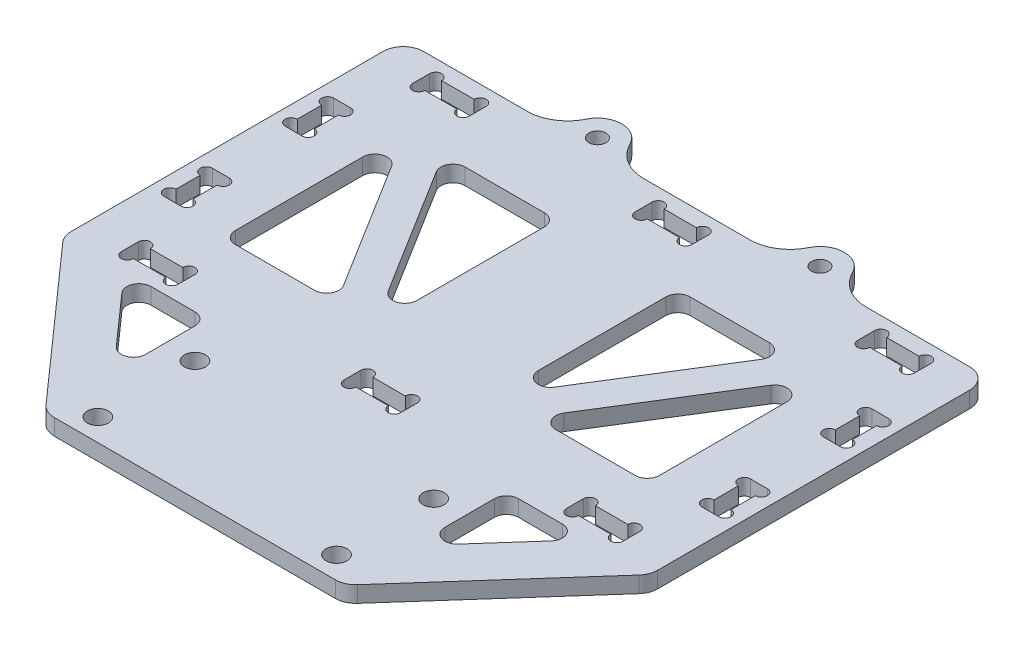
SolidWorks part; units mm, degrees
ref_plane "前视基准面" through (0, 0, 0) normal (0, 0, 1) x (1, 0, 0)
ref_plane "上视基准面" through (0, 0, 0) normal (0, 1, 0) x (1, 0, 0)
ref_plane "右视基准面" through (0, 0, 0) normal (1, 0, 0) x (0, 0, -1)
other "Configuration Table"
sketch "草图1" plane through (0, 0, 0) normal (0, 1, 0) x (1, 0, 0)
  line L0 (-37, 0) -> (37, 0)
  line L1 (37, 0) -> (37, 40)
  line L2 (37, 40) -> (72.5, 40)
  line L3 (72.5, 40) -> (72.5, 124)
  line L4 (0, 0) -> (0, 122.7817) construction
  line L5 (72.5, 124) -> (-72.5, 124)
  line L6 (-72.5, 40) -> (-72.5, 124)
  line L7 (-37, 40) -> (-72.5, 40)
  line L8 (-37, 0) -> (-37, 40)
  point P10 (0, 124)
  point P13 (0, 0)
  dimension "D1" = 74
  dimension "D2" = 40
  dimension "D3" = 84
  dimension "D4" = 145
extrude "凸台-拉伸1" add sketch "草图1" along normal blind 4
sketch "草图2" plane through (0, 4, 0) normal (0, 1, 0) x (1, 0, 0)
  line L0 (0, 0) -> (0, 124) construction
  line L1 (-37, 0) -> (37, 0) construction
  line L2 (72.5, 124) -> (-72.5, 124) construction
  line L3 (-37, 17.5) -> (37, 17.5) construction
  circle A0 centre (29.5, 5.5) radius 2.6
  circle A1 centre (-29.5, 5.5) radius 2.6
  circle A2 centre (29.5, 29.5) radius 2.6
  circle A3 centre (-29.5, 29.5) radius 2.6
  dimension "D1" = 59
  dimension "D3" = 24
  dimension "D4" = 5.2
  dimension "D2" = 17.5
extrude "切除-拉伸1" cut sketch "草图2" against normal blind 4
sketch "草图3" plane through (0, 4, 0) normal (0, 1, 0) x (1, 0, 0)
  line L19 (-72.5, 81.9) -> (72.5, 81.9) construction
  line L20 (-72.5, 124) -> (-72.5, 40) construction
  line L21 (72.5, 40) -> (72.5, 124) construction
  line L22 (-7, 43.8) -> (7, 48) construction
  line L23 (-7, 48) -> (7, 43.8) construction
  line L24 (0, 0) -> (0, 124) construction
  line L25 (-37, 0) -> (37, 0) construction
  line L26 (72.5, 124) -> (-72.5, 124) construction
  line L28 (-7, 115.8) -> (7, 115.8)
  line L29 (-7, 115.8) -> (-7, 120)
  line L30 (-7, 120) -> (7, 120)
  line L31 (7, 115.8) -> (7, 120)
  line L32 (-7, 115.8) -> (7, 120) construction
  line L33 (-7, 120) -> (7, 115.8) construction
  line L46 (48, 115.8) -> (62, 115.8)
  line L47 (48, 115.8) -> (48, 120)
  line L48 (48, 120) -> (62, 120)
  line L49 (62, 115.8) -> (62, 120)
  line L58 (-62, 115.8) -> (-62, 120)
  line L59 (-48, 120) -> (-62, 120)
  line L60 (-48, 115.8) -> (-48, 120)
  line L61 (-48, 115.8) -> (-62, 115.8)
  line L62 (-48, 48) -> (-62, 48)
  line L63 (-48, 48) -> (-48, 43.8)
  line L64 (-48, 43.8) -> (-62, 43.8)
  line L65 (-62, 48) -> (-62, 43.8)
  line L66 (62, 48) -> (62, 43.8)
  line L67 (48, 43.8) -> (62, 43.8)
  line L68 (48, 48) -> (48, 43.8)
  line L69 (48, 48) -> (62, 48)
  line L70 (7, 48) -> (7, 43.8)
  line L71 (-7, 43.8) -> (7, 43.8)
  line L72 (-7, 48) -> (-7, 43.8)
  line L73 (-7, 48) -> (7, 48)
  line L74 (-62, 117.9) -> (-48, 117.9) construction
  circle A0 centre (-5.5, 120) radius 1.5
  circle A1 centre (-5.5, 115.8) radius 1.5
  circle A2 centre (5.5, 120) radius 1.5
  circle A3 centre (5.5, 115.8) radius 1.5
  circle A4 centre (49.5, 115.8) radius 1.5
  circle A5 centre (49.5, 120) radius 1.5
  circle A6 centre (60.5, 120) radius 1.5
  circle A7 centre (60.5, 115.8) radius 1.5
  circle A16 centre (-60.5, 115.8) radius 1.5
  circle A17 centre (-60.5, 120) radius 1.5
  circle A18 centre (-49.5, 120) radius 1.5
  circle A19 centre (-49.5, 115.8) radius 1.5
  circle A20 centre (-49.5, 48) radius 1.5
  circle A21 centre (-49.5, 43.8) radius 1.5
  circle A22 centre (-60.5, 43.8) radius 1.5
  circle A23 centre (-60.5, 48) radius 1.5
  circle A24 centre (60.5, 48) radius 1.5
  circle A25 centre (60.5, 43.8) radius 1.5
  circle A26 centre (49.5, 43.8) radius 1.5
  circle A27 centre (49.5, 48) radius 1.5
  circle A28 centre (5.5, 48) radius 1.5
  circle A29 centre (5.5, 43.8) radius 1.5
  circle A30 centre (-5.5, 48) radius 1.5
  circle A31 centre (-5.5, 43.8) radius 1.5
  point P6 (0, 117.9)
  point P85 (0, 45.9)
  dimension "D4" = 3
  dimension "D1" = 14
  dimension "D2" = 4.2
  dimension "D3" = 4
  dimension "D6" = 55
  dimension "D5" = 2
  dimension "D7" = 36
extrude "切除-拉伸2" cut sketch "草图3" against normal blind 4 contours L30 A0 | A3 L31 A2 L30 A0 L29 A1 L28 | L30 A0 | L28 A1 | L28 A1 | L30 A2 | L30 A2 | L28 A3 | L28 A3
sketch "草图4" plane through (0, 4, 0) normal (0, 1, 0) x (1, 0, 0)
  line L0 (-72.5, 40) -> (-37, 0)
  line L1 (-57.5, 40) -> (-37, 16.9014)
  line L2 (-72.5, 40) -> (-37, 40) construction
  line L3 (-37, 40) -> (-37, 0) construction
  line L4 (-72.5, 40) -> (-57.5, 40)
  line L5 (-37, 16.9014) -> (-37, 0)
  line L6 (0, 0) -> (0, 124) construction
  line L7 (-37, 0) -> (37, 0) construction
  line L8 (72.5, 124) -> (-72.5, 124) construction
  line L9 (37, 16.9014) -> (37, 0)
  line L10 (72.5, 40) -> (57.5, 40)
  line L11 (57.5, 40) -> (37, 16.9014)
  line L12 (72.5, 40) -> (37, 0)
  dimension "D1" = 15
extrude "凸台-拉伸2" add sketch "草图4" against normal blind 4
sketch "草图5" plane through (0, 4, 0) normal (0, 1, 0) x (1, 0, 0)
  line L3 (-48, 115.8) -> (-48, 120) construction
  line L4 (72.5, 124) -> (-72.5, 124) construction
  circle A1 centre (-27.5, 127) radius 6
  circle A2 centre (-27.5, 127) radius 2.1
  circle A3 centre (27.5, 127) radius 6
  circle A4 centre (27.5, 127) radius 2.1
  dimension "D1" = 4.2
  dimension "D3" = 3
  dimension "D4" = 12
  dimension "D2" = 20.5
extrude "凸台-拉伸3" add sketch "草图5" against normal blind 4
fillet "圆角1" radius 10 4 edges at (-22.3038, 2, -124) (-32.6962, 2, -124) (32.6962, 2, -124) (22.3038, 2, -124)
fillet "圆角2" radius 3 6 edges at (37, 2, -16.9014) (57.5, 2, -40) (37, 2, -40) (-37, 2, -16.9014) (-57.5, 2, -40) (-37, 2, -40)
sketch "草图6" plane through (0, 4, 0) normal (0, 1, 0) x (1, 0, 0)
  line L0 (59, 115.8) -> (59, 48) construction
  line L1 (59, 81.9) -> (96.5672, 81.9) construction
  line L2 (0, 124) -> (0, 0) construction
  line L3 (68.6, 60.9) -> (68.6, 72.9)
  line L4 (64.4, 102.9) -> (68.6, 102.9)
  line L5 (64.4, 102.9) -> (64.4, 90.9)
  line L6 (64.4, 90.9) -> (68.6, 90.9)
  line L7 (68.6, 102.9) -> (68.6, 90.9)
  line L8 (64.4, 72.9) -> (68.6, 72.9)
  line L9 (64.4, 60.9) -> (64.4, 72.9)
  line L10 (64.4, 60.9) -> (68.6, 60.9)
  line L11 (66.5, 102.9) -> (66.5, 90.9) construction
  line L12 (72.5, 40) -> (72.5, 124) construction
  line L13 (13.1125, 124) -> (-13.1125, 124) construction
  line L14 (-37, 0) -> (37, 0) construction
  circle A0 centre (64.4, 101.4) radius 1.5
  circle A1 centre (68.6, 101.4) radius 1.5
  circle A2 centre (64.4, 92.4) radius 1.5
  circle A3 centre (68.6, 92.4) radius 1.5
  circle A4 centre (68.6, 71.4) radius 1.5
  circle A5 centre (64.4, 71.4) radius 1.5
  circle A6 centre (64.4, 62.4) radius 1.5
  circle A7 centre (68.6, 62.4) radius 1.5
  dimension "D5" = 3
  dimension "D1" = 12
  dimension "D2" = 4.2
  dimension "D3" = 18
  dimension "D4" = 6
extrude "切除-拉伸3" cut sketch "草图6" against normal blind 10 contours A6 L9 | L10 A7 L3 A4 L8 A5 L9 A6 | A6 L9 | A7 L3 | A7 L3 | A4 L3 | A4 L3 | A5 L9 | A5 L9 | L5 A2 | L5 A0 | L5 A2 | A3 L7 A1 L4 A0 L5 A2 L6 | L7 A3 | L7 A1 | L7 A1 | L5 A0 | L7 A3
sketch "草图7" plane through (0, 4, 0) normal (0, 1, 0) x (1, 0, 0)
  line L0 (-52.4222, 104.4) -> (-52.4222, 59.4)
  line L1 (-52.4222, 59.4) -> (-24.4222, 59.4)
  line L2 (-24.4222, 59.4) -> (-52.4222, 104.4)
  line L3 (-43, 104.4) -> (-15, 59.4)
  line L4 (-15, 59.4) -> (-15, 104.4)
  line L5 (-15, 104.4) -> (-43, 104.4)
  line L6 (0, 115.8) -> (0, 48) construction
  line L7 (-4, 115.8) -> (4, 115.8) construction
  line L8 (-4, 48) -> (4, 48) construction
  line L9 (15, 104.4) -> (43, 104.4)
  line L10 (15, 59.4) -> (15, 104.4)
  line L11 (43, 104.4) -> (15, 59.4)
  line L12 (24.4222, 59.4) -> (52.4222, 104.4)
  line L13 (52.4222, 59.4) -> (24.4222, 59.4)
  line L14 (52.4222, 104.4) -> (52.4222, 59.4)
  line L15 (0, 81.9) -> (13.1956, 81.9) construction
  dimension "D1" = 28
  dimension "D2" = 45
  dimension "D3" = 8
  dimension "D4" = 30
extrude "切除-拉伸4" cut sketch "草图7" against normal blind 5
fillet "圆角3" radius 3 12 edges at (24.4222, 2, -59.4) (52.4222, 2, -59.4) (43, 2, -104.4) (15, 2, -104.4) (52.4222, 2, -104.4) (15, 2, -59.4) (-15, 2, -104.4) (-43, 2, -104.4) (-15, 2, -59.4) (-24.4222, 2, -59.4) (-52.4222, 2, -59.4) (-52.4222, 2, -104.4)
mirror "镜向1" about plane through (0, 0, 0) normal (1, 0, 0) of "切除-拉伸3"
fillet "圆角4" radius 5 6 edges at (-37, 2, 0) (-72.5, 2, -40) (37, 2, 0) (72.5, 2, -40) (72.5, 2, -124) (-72.5, 2, -124)
